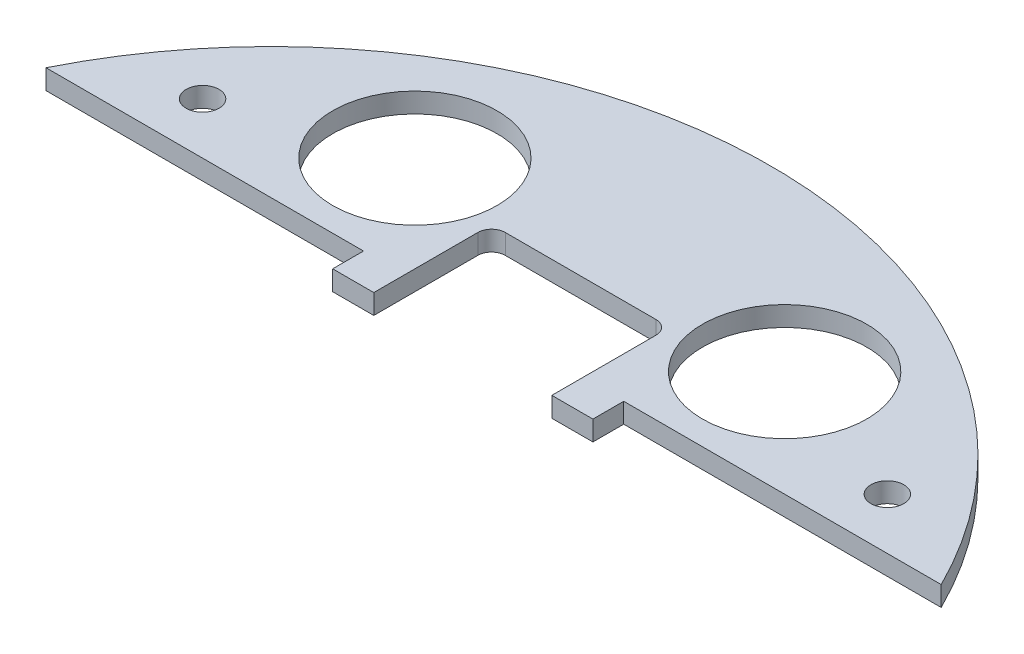
SolidWorks part; units mm, degrees
material "Acrylic (Medium-high impact)"
ref_plane "Front Plane" through (0, 0, 0) normal (0, 0, 1) x (1, 0, 0)
ref_plane "Top Plane" through (0, 0, 0) normal (0, 1, 0) x (1, 0, 0)
ref_plane "Right Plane" through (0, 0, 0) normal (1, 0, 0) x (0, 0, -1)
sketch "Sketch1" plane through (0, 0, 0) normal (0, 1, 0) x (1, 0, 0)
  line L0 (0, -85) -> (-32.7511, -65.2408) construction
  line L1 (0, -85) -> (0, 0) construction
  arc A0 (36.8566, -63.0126) -> (-36.8566, -63.0126) centre (0, 0) ccw
  arc A1 (30.3631, -61.7375) -> (-30.3631, -61.7375) centre (0, -85) ccw
  arc A2 (36.8566, -63.0126) -> (30.3631, -61.7375) centre (34.3322, -58.6967) cw
  arc A3 (-30.3631, -61.7375) -> (-36.8566, -63.0126) centre (-34.3322, -58.6967) cw
  dimension "D1" = 146
  dimension "D2" = 76.5
  dimension "D4" = 5
  dimension "D3" = 85
extrude "Boss-Extrude1" add sketch "Sketch1" along normal blind 2.9
sketch "solenoid placement" plane through (0, 2.9, 0) normal (0, 1, 0) x (1, 0, 0)
  line L4 (-19, -36) -> (19, -36)
  line L5 (-19, -36) -> (19, -36)
  line L6 (19, -36) -> (19, 28)
  line L7 (19, -36) -> (19, 28)
  line L8 (19, 28) -> (-19, 28)
  line L9 (19, 28) -> (-19, 28)
  line L10 (-19, 28) -> (-19, -36)
  line L11 (-19, 28) -> (-19, -36)
  circle A1 centre (0, 0) radius 73 construction
  arc A2 (36.8566, -63.0126) -> (-36.8566, -63.0126) centre (0, 0) ccw construction
  dimension "D1" = 0
extrude "Cut-Extrude1" cut sketch "solenoid placement" against normal through all
sketch "Sketch4" plane through (0, 2.9, 0) normal (0, 1, 0) x (1, 0, 0)
  line L1 (-13, 28) -> (13, 28)
  line L2 (-13, 28) -> (-13, 43.2)
  line L3 (13, 45.2) -> (-13, 45.2) construction
  line L4 (13, 28) -> (13, 43.2)
  line L5 (11, 45.2) -> (-11, 45.2)
  line L6 (19, 28) -> (-19, 28) construction
  arc A0 (11, 45.2) -> (13, 43.2) centre (11, 43.2) cw
  arc A1 (-11, 45.2) -> (-13, 43.2) centre (-11, 43.2) ccw
  point P6 (0, 28)
  dimension "D1" = 2
extrude "Cut-Extrude4" cut sketch "Sketch4" against normal through all
sketch "Sketch5" plane through (0, 2.9, 0) normal (0, 1, 0) x (1, 0, 0)
  circle A2 centre (-27, 48) radius 12
  circle A3 centre (-27, 48) radius 12
  circle A4 centre (27, 48) radius 12
  circle A21 centre (27, 48) radius 12
  dimension "D1" = 0
  dimension "D2" = 0
extrude "Cut-Extrude5" cut sketch "Sketch5" against normal through all
sketch "Sketch6" plane through (0, 2.9, 0) normal (0, 1, 0) x (1, 0, 0)
  circle A1 centre (40, -40) radius 2.4
  circle A2 centre (40, -40) radius 2.4
  circle A3 centre (-40, -40) radius 2.4
  circle A4 centre (-40, -40) radius 2.4
  circle A5 centre (-50, 40) radius 2.4
  circle A6 centre (-50, 40) radius 2.4
  circle A7 centre (50, 40) radius 2.4
  circle A8 centre (50, 40) radius 2.4
  dimension "D1" = 0
  dimension "D2" = 0
  dimension "D3" = 0
  dimension "D4" = 0
extrude "Cut-Extrude6" cut sketch "Sketch6" against normal through all
sketch "Sketch3" plane through (0, 2.9, 0) normal (0, 1, 0) x (1, 0, 0)
  line L0 (-19, 28) -> (19, 28)
  line L1 (-73, -32.5) -> (73, -32.5)
  line L2 (-73, -32.5) -> (-73, 32.5)
  line L3 (-73, 32.5) -> (-19, 32.5)
  line L4 (73, -32.5) -> (73, 32.5)
  line L5 (-73, -32.5) -> (73, 32.5) construction
  line L6 (-73, 32.5) -> (73, -32.5) construction
  line L7 (19, 28) -> (19, 32.5)
  line L8 (-19, 28) -> (-19, 32.5)
  line L9 (19, 32.5) -> (73, 32.5)
  arc A0 (36.8566, -63.0126) -> (-36.8566, -63.0126) centre (0, 0) ccw construction
  point P0 (0, 0)
  dimension "D1" = 65
extrude "Cut-Extrude3" cut sketch "Sketch3" against normal through all
delete or keep bodies "Body-Delete/Keep 1" type delete bodies bodies 115
equation "\"smallPulleyTeeth\"= 15"
equation "\"largePulleyTeeth\"= 30"
equation "\"eighthThick\"= 2.9mm"
equation "\"sixteenthThick\" = 1.7mm"
equation "\"quarterThick\"=6.0mm"
equation "\"OD\" = 146mm"
equation "\"puckAngle\" = 60.5deg"
equation "\"D1@Sketch1\"=\"OD\""
equation "\"puckDiam\" = 76.5mm"
equation "\"D2@Sketch1\"=\"puckDiam\""
equation "\"D1@Boss-Extrude1\"=\"eighthThick\""
equation "\"axlePress\" = 5.9mm"
equation "\"press\" = 0.2mm"
equation "\"wheelClear\" = 0.3mm"
equation "\"10-32clear\" = 4.8mm"
equation "\"6-32clear\" = 3.3mm"
equation "\"8-32clear\" = 4.0mm"
equation "\"wheelHeight\" = 22mm"
equation "\"wheelWell\" = 65mm"
equation "\"D1@Sketch3\"=\"wheelWell\""
equation "\"puckDist\" = 85mm"
equation "\"scoopFillet\" = 5mm"
equation "\"4-40clear\" = 3.0mm"
equation "\"D3@Sketch1\"=\"puckDist\""
equation "\"D4@Sketch1\"=\"scoopFillet\""
